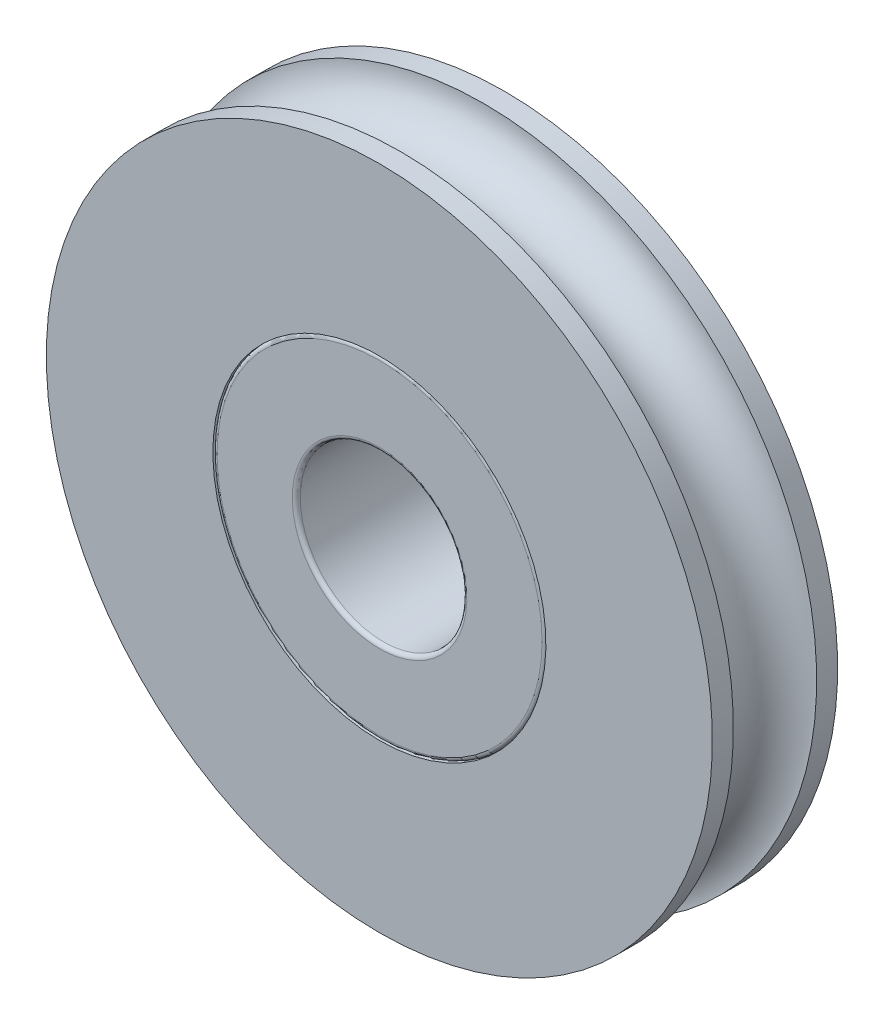
SolidWorks part; units mm, degrees
ref_plane "Front Plane" through (0, 0, 0) normal (0, 0, 1) x (1, 0, 0)
ref_plane "Top Plane" through (0, 0, 0) normal (0, 1, 0) x (1, 0, 0)
ref_plane "Right Plane" through (0, 0, 0) normal (1, 0, 0) x (0, 0, -1)
sketch "Sketch1" plane through (0, 0, 0) normal (1, 0, 0) x (0, 0, -1)
  line L0 (0, 0) -> (4.7625, 0) construction
  line L1 (3.9683, 12.7) -> (4.7688, 12.7)
  line L2 (-0.0064, 6.35) -> (4.7689, 6.35)
  line L3 (0.7937, 12.6619) -> (3.9687, 12.6619) construction
  line L4 (-0.0064, 12.7) -> (0.7942, 12.7)
  line L12 (0, 6.35) -> (4.7625, 6.35) construction
  line L16 (4.7625, 3.175) -> (0, 3.175) construction
  line L20 (-0.0064, 6.35) -> (-0.0064, 12.7)
  line L21 (4.7689, 6.35) -> (4.7688, 12.7)
  line L22 (2.3812, 11.0744) -> (2.3812, 14.2494) construction
  line L24 (0, 3.175) -> (0, 6.35) construction
  line L25 (4.7625, 6.35) -> (4.7625, 3.175) construction
  line L28 (2.3812, 12.6619) -> (2.3813, 0) construction
  circle A0 centre (2.3812, 12.6619) radius 1.5875 construction
  arc A1 (0.7942, 12.7) -> (3.9683, 12.7) centre (2.3812, 12.6619) ccw
  point P11 (2.3812, 11.0744)
  point P12 (2.3812, -11.0744)
  dimension "Belt" = 3.175
  dimension "B" = 22.1488
  dimension "Bore" = 6.35
  dimension "W" = 4.7752
  dimension "Bearing Wd." = 4.7625
  dimension "Bearing OD" = 12.7
  dimension "OD" = 25.4
  dimension "Pulley Depth" = 1.6256
revolve "Revolve1" add sketch "Sketch1" angle 360 about L0
sketch "Sketch2" plane through (0, 0, 0) normal (1, 0, 0) x (0, 0, -1)
  line L0 (0, 0) -> (4.7625, 0) construction
  line L2 (0, 6.35) -> (4.7625, 6.35)
  line L3 (0, 6.35) -> (0, 3.175)
  line L4 (0, 3.175) -> (4.7625, 3.175)
  line L5 (4.7625, 6.35) -> (4.7625, 3.175)
revolve "Revolve2" add sketch "Sketch2" angle 360 about L0
fillet "Fillet1" radius 0.1524 4 edges at (0, -3.175, 0) (0, -3.175, -4.7625) (0, -6.35, -4.7625) (0, -6.35, 0)
